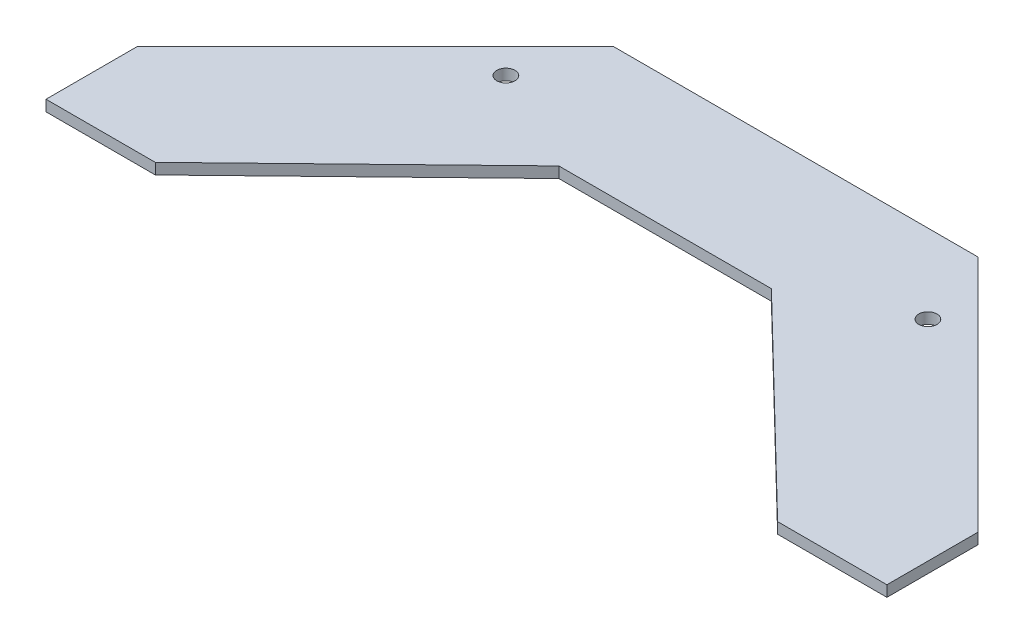
SolidWorks part; units mm, degrees
ref_plane "Front Plane" through (0, 0, 0) normal (0, 0, 1) x (1, 0, 0)
ref_plane "Top Plane" through (0, 0, 0) normal (0, 1, 0) x (1, 0, 0)
ref_plane "Right Plane" through (0, 0, 0) normal (1, 0, 0) x (0, 0, -1)
sketch "Sketch1" plane through (0, 0, 0) normal (0, 1, 0) x (1, 0, 0)
  line L0 (0, 0) -> (60, 0)
  line L1 (60, 0) -> (99.2444, -39.2444)
  line L2 (99.2444, -39.2444) -> (99.2444, -54.2444)
  line L3 (99.2444, -54.2444) -> (81.2444, -54.2444)
  line L4 (81.2444, -54.2444) -> (47.5, -21.5288)
  line L5 (47.5, -21.5288) -> (12.5, -21.5288)
  line L6 (12.5, -21.5288) -> (-21.2444, -54.2444)
  line L7 (-21.2444, -54.2444) -> (-39.2444, -54.2444)
  line L8 (-39.2444, -54.2444) -> (-39.2444, -39.2444)
  line L9 (-39.2444, -39.2444) -> (0, 0)
  point P3 (0, 0)
  dimension "D1" = 60
  dimension "D2" = 55.5
  dimension "D3" = 135
  dimension "D4" = 135
  dimension "D5" = 15
  dimension "D6" = 18
  dimension "D7" = 35
  dimension "D8" = 47
extrude "Boss-Extrude1" add sketch "Sketch1" along normal blind 1.8
sketch "Sketch2" plane through (0, 1.8, 0) normal (0, 1, 0) x (1, 0, 0)
  line L0 (30, 0) -> (30, -13) construction
  line L1 (60, 0) -> (0, 0) construction
  line L2 (-4.75, -13) -> (64.75, -13) construction
  circle A0 centre (-4.75, -13) radius 1.5
  circle A1 centre (64.75, -13) radius 1.5
  point P6 (30, -13)
  dimension "D3" = 3
  dimension "D1" = 69.5
  dimension "D2" = 13
extrude "Cut-Extrude2" cut sketch "Sketch2" against normal blind 1.8
